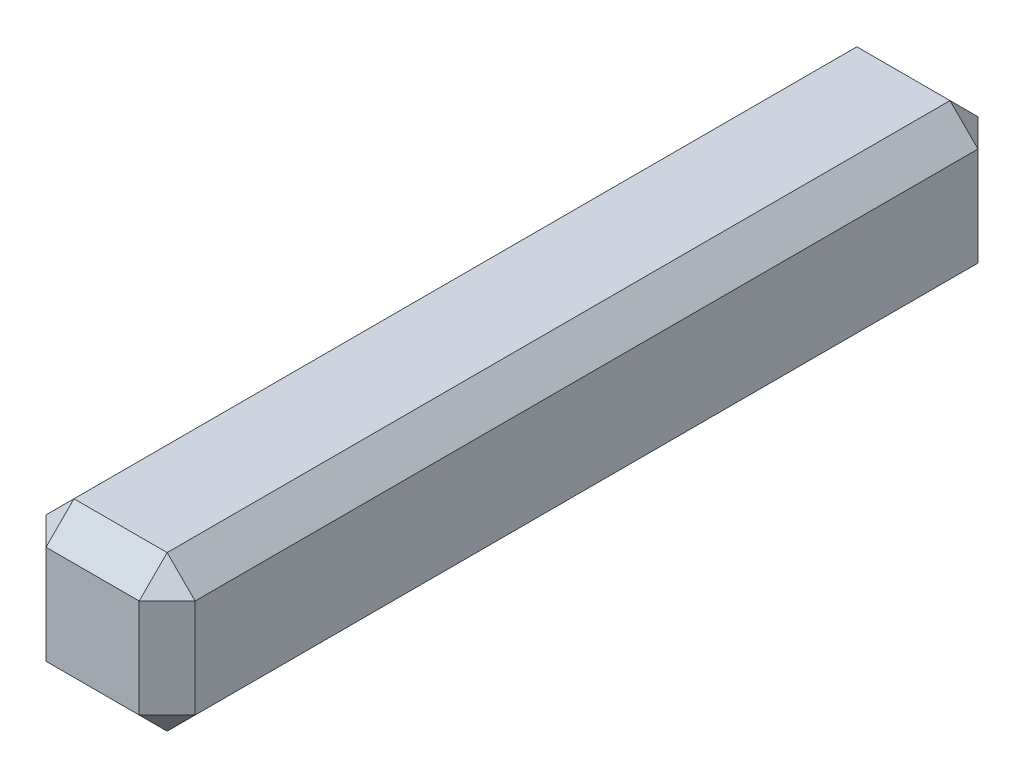
SolidWorks part; units mm, degrees
ref_plane "Front Plane" through (0, 0, 0) normal (0, 0, 1) x (1, 0, 0)
ref_plane "Top Plane" through (0, 0, 0) normal (0, 1, 0) x (1, 0, 0)
ref_plane "Right Plane" through (0, 0, 0) normal (1, 0, 0) x (0, 0, -1)
sketch "Sketch1" plane through (0, 0, 0) normal (0, 0, 1) x (1, 0, 0)
  line L1 (-4.3403, 4.503) -> (3.6597, 4.503)
  line L2 (-4.3403, 4.503) -> (-4.3403, -3.797)
  line L3 (-4.3403, -3.797) -> (3.6597, -3.797)
  line L4 (3.6597, 4.503) -> (3.6597, -3.797)
  dimension "D1" = 8
  dimension "D2" = 8.3
extrude "Boss-Extrude1" add sketch "Sketch1" along normal blind 45
chamfer "Chamfer1" distance 1.5 angle 45 12 edges at (3.6597, 0.353, 45) (-4.3403, 0.353, 45) (-0.3403, -3.797, 45) (-0.3403, 4.503, 45) (3.6597, 0.353, 0) (3.6597, -3.797, 22.5) (-0.3403, -3.797, 0) (-4.3403, -3.797, 22.5) (-4.3403, 0.353, 0) (-4.3403, 4.503, 22.5) (-0.3403, 4.503, 0) (3.6597, 4.503, 22.5)
